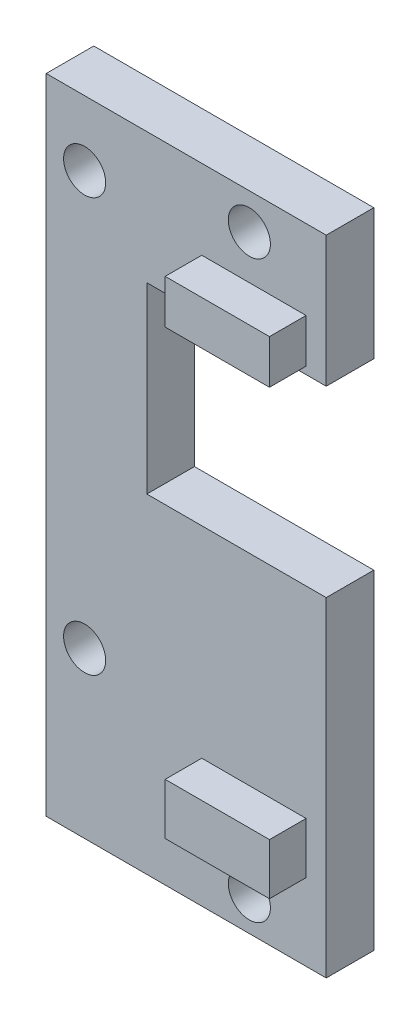
SolidWorks part; units mm, degrees
ref_plane "前视基准面" through (0, 0, 0) normal (0, 0, 1) x (1, 0, 0)
ref_plane "上视基准面" through (0, 0, 0) normal (0, 1, 0) x (1, 0, 0)
ref_plane "右视基准面" through (0, 0, 0) normal (1, 0, 0) x (0, 0, -1)
other "Configuration Table"
sketch "接口端底座，Type-C区开口 profile" plane through (0, 0, 0) normal (0, 0, 1) x (1, 0, 0)
  line L0 (-40.5, -32) -> (-25.2, -32)
  line L1 (-25.2, -32) -> (-25.2, -14)
  line L2 (-25.2, -14) -> (-35, -14)
  line L3 (-35, -14) -> (-35, -4)
  line L4 (-35, -4) -> (-25.2, -4)
  line L5 (-25.2, -4) -> (-25.2, 3.15)
  line L6 (-25.2, 3.15) -> (-40.5, 3.15)
  line L7 (-40.5, 3.15) -> (-40.5, -32)
  circle A0 centre (-38.4, -23) radius 1.15
  circle A1 centre (-38.4, -0.4) radius 1.15
  circle A2 centre (-29.4, -30.2) radius 1.15
  circle A3 centre (-29.4, 1.2) radius 1.15
extrude "接口端底座，Type-C区开口" add sketch "接口端底座，Type-C区开口 profile" along normal blind 2.6
sketch "只托住开发板两端的边缘 profile" plane through (0, 0, 0) normal (0, 0, 1) x (1, 0, 0)
  line L0 (-32, -27.8) -> (-26.3, -27.8)
  line L1 (-26.3, -27.8) -> (-26.3, -25)
  line L2 (-26.3, -25) -> (-32, -25)
  line L3 (-32, -25) -> (-32, -27.8)
  line L4 (-32, -3.6) -> (-26.3, -3.6)
  line L5 (-26.3, -3.6) -> (-26.3, -1.2)
  line L6 (-26.3, -1.2) -> (-32, -1.2)
  line L7 (-32, -1.2) -> (-32, -3.6)
extrude "只托住开发板两端的边缘" add sketch "只托住开发板两端的边缘 profile" along normal blind 2 from offset 2.6
